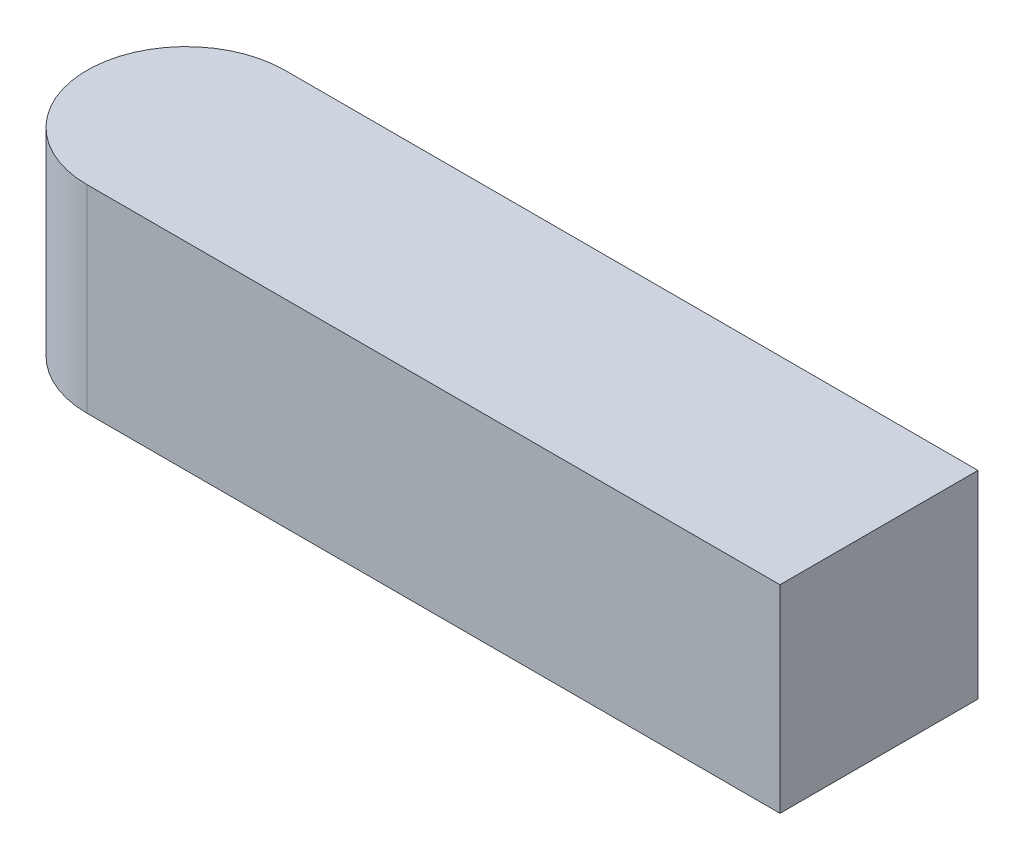
SolidWorks part; units mm, degrees
material "Cast Alloy Steel"
ref_plane "Front Plane" through (0, 0, 0) normal (0, 0, 1) x (1, 0, 0)
ref_plane "Top Plane" through (0, 0, 0) normal (0, 1, 0) x (1, 0, 0)
ref_plane "Right Plane" through (0, 0, 0) normal (1, 0, 0) x (0, 0, -1)
sketch "Sketch1" plane through (0, 0, 0) normal (0, 1, 0) x (1, 0, 0)
  line L0 (-80, 0) -> (80, 0) construction
  line L1 (-70, 0) -> (70, 0) construction
  line L2 (-70, 10) -> (70, 10)
  line L3 (-70, -10) -> (70, -10)
  arc A0 (-70, 10) -> (-70, -10) centre (-70, 0) ccw
  arc A1 (70, -10) -> (70, 10) centre (70, 0) ccw
  point P4 (0, 0)
  point P7 (0, 0)
  dimension "D" = 10
  dimension "L" = 160
extrude "Boss-Extrude1" add sketch "Sketch1" along normal blind 20
sketch "Sketch2" plane through (0, 20, 0) normal (0, 1, 0) x (1, 0, 0)
  line L0 (70, 10) -> (-70, 10) construction
  line L1 (0, 10) -> (80, 10)
  line L2 (0, 10) -> (0, -10)
  line L3 (0, -10) -> (80, -10)
  line L4 (80, 10) -> (80, -10)
  line L5 (-70, -10) -> (70, -10) construction
  arc A0 (70, -10) -> (70, 10) centre (70, 0) ccw construction
extrude "Cut-Extrude1" cut sketch "Sketch2" against normal through all
equation "\"L\"= 160"
equation "\"D\"= 10"
equation "\"H\"= 20"
equation "\"Cut-Extrude1\"= IIF ( \"L\" = 160 , \"unsuppressed\" , IIF ( \"L\" = 100 , \"unsuppressed\" , \"suppressed\" ) )"
equation "\"L@Sketch1\"=\"L\""
equation "\"D@Sketch1\"=\"D\""
equation "\"H@Boss-Extrude1\"=\"H\""
